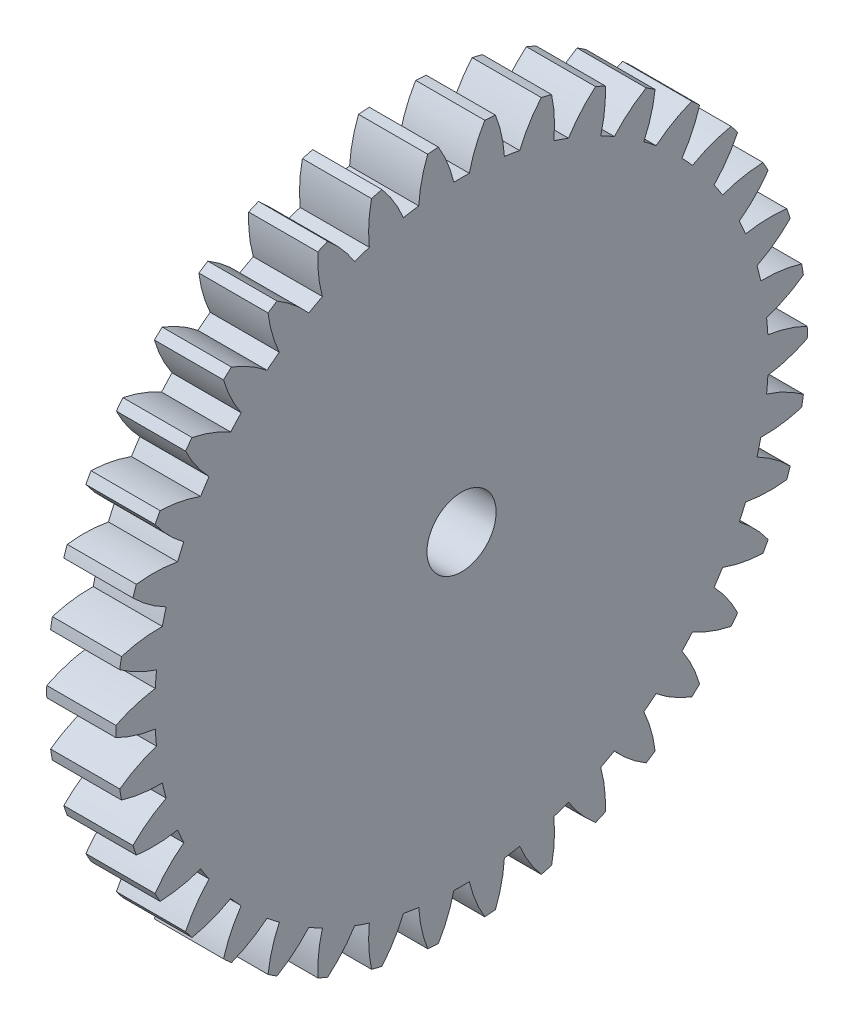
SolidWorks part; units mm, degrees
ref_plane "Plane1" through (0, 0, 0) normal (0, 0, 1) x (1, 0, 0)
ref_plane "Plane2" through (0, 0, 0) normal (0, 1, 0) x (1, 0, 0)
ref_plane "Plane3" through (0, 0, 0) normal (1, 0, 0) x (0, 0, -1)
other "Configuration Table"
sketch "HoldingSke" plane through (0, 0, 0) normal (0, 1, 0) x (1, 0, 0)
  line L0 (0, 0) -> (320.2476, -250.2048)
  line L1 (-15, 0) -> (100, 0) construction
  line L2 (0, 0) -> (-2.1039, 2.3779)
  line L3 (0, 0) -> (-11.863, 4.5341)
  line L4 (0, 0) -> (6.8053, 5.3169)
  line L5 (0, 0) -> (-47.5972, -17.7524)
  line L6 (0, 0) -> (-5.2639, -3.5516)
  line L7 (-2.1039, 2.3779) -> (8.8308, 51.9871)
  line L8 (-76.2, 54.61) -> (-69.596, 54.61)
  line L9 (-71.009, 38.7566) -> (-53.1078, 45.2721)
  line L10 (-76.2, 71.12) -> (104.1128, 71.12)
  line L11 (0, 0) -> (-6.35, 0)
  line L12 (-76.2, 101.6) -> (-76.1428, 101.6)
  line L13 (24.9733, 27.94) -> (52.9518, 28.4284)
  line L14 (24.9733, 27.94) -> (24.9746, 27.94)
  line L15 (24.9733, 27.94) -> (100.4006, 29.5858)
  circle A0 centre (0, 0) radius 3.175
  circle A1 centre (0, 0) radius 28.1769
  circle A2 centre (0, 0) radius 38.1
  circle A3 centre (0, 0) radius 3.175
  dimension "MHD" = 56.3537
  dimension "Hub_dia" = 76.2
  dimension "Bore" = 6.35
  dimension "MBD" = 6.35
  dimension "Num_teeth" = 38
  dimension "Pitch" = 406.4
  dimension "Overall_len" = 50.8
  dimension "Show_teeth" = 38
  dimension "Thickness" = 6.35
  dimension "OAL" = 50.8001
  dimension "T_dim" = 6.604
  dimension "Ap" = 20
  dimension "H" = 19.05
  dimension "Pitch_radius" = 180.3128
  dimension "Width" = 6.35
  dimension "Backlash" = 0.0571
  dimension "Addendum_fac" = 1
  dimension "Dedendum_fac" = 1.25
  dimension "Clearance_fac" = 0.25
  dimension "Dedendum_add" = 0.0013
sketch "BasProSke" plane through (0, 0, 0) normal (0, 1, 0) x (1, 0, 0)
  line L0 (-10, 0) -> (60, 0) construction
  line L1 (0, 0) -> (0, 31.75)
  line L2 (0, 0) -> (6.35, 0)
  line L3 (6.35, 0) -> (6.35, 31.75)
  line L4 (6.35, 31.75) -> (0, 31.75)
  dimension "Thickness" = 6.35
  dimension "Diameter" = 63.5
revolve "Base-Revolve" add sketch "BasProSke" angle 360 about L0
sketch "TooCutSke" plane through (0, 0, 0) normal (1, 0, 0) x (0, 0, -1)
  line L1 (0, 0) -> (0, 107) construction
  line L2 (0, 0) -> (-1.3465, 30.1324) construction
  line L3 (0, 0) -> (-4.978, 60.0755) construction
  line L4 (-1.3465, 30.1324) -> (-2.489, 30.0378) construction
  arc A0 (0.7117, 28.1679) -> (-0.7117, 28.1679) centre (0, 0) ccw
  arc A1 (2.1467, 31.7028) -> (-2.1467, 31.7028) centre (0, 0) ccw
  circle A2 centre (0, 0) radius 30.1625 construction
  circle A3 centre (0, 0) radius 28.3435 construction
  arc A4 (-0.7117, 28.1679) -> (-2.1467, 31.7028) centre (-12.4675, 25.4541) ccw
  arc A5 (2.1467, 31.7028) -> (0.7117, 28.1679) centre (12.4675, 25.4541) ccw
  dimension "Root_dia" = 56.3537
  dimension "Overcut_dia" = 63.5508
  dimension "Pitch_dia" = 60.325
  dimension "Base_dia" = 56.687
  dimension "Flank_rad" = 12.065
  dimension "Half_ang" = 4.737
  dimension "Half_CT" = 1.1465
extrude "ToothCut" cut sketch "TooCutSke" along normal through all
fillet "Breaks" [suppressed] radius 0.0318
fillet "RootFillets" [suppressed] radius 0.3981
pattern_circular "TeethCuts" count 38 every 9.474 about axis through (-10, 0, 0) along (1, 0, 0) of "ToothCut", "RootFillets", "Breaks"
sketch "HubNeaOneSke" plane through (0, 0, 0) normal (-1, 0, 0) x (0, 0, 1)
  circle A0 centre (0, 0) radius 28.1769
  dimension "Diameter" = 56.3537
extrude "HubNearOne" [suppressed] add sketch "HubNeaOneSke" along normal blind 44.4501
sketch "HubNeaBotSke" plane through (0, 0, 0) normal (-1, 0, 0) x (0, 0, 1)
  circle A0 centre (0, 0) radius 28.1769
  dimension "Diameter" = 56.3537
extrude "HubNearBoth" [suppressed] add sketch "HubNeaBotSke" along normal blind 22.225
ref_plane "FarPln" through (6.35, 0, 0) normal (1, 0, 0) x (0, 0, -1)
sketch "HubFarSke" plane through (6.35, 0, 0) normal (1, 0, 0) x (0, 0, -1)
  circle A0 centre (0, 0) radius 28.1769
  dimension "Diameter" = 56.3537
extrude "HubFar" [suppressed] add sketch "HubFarSke" along normal blind 22.225
sketch "BorSke" plane through (0, 0, 0) normal (1, 0, 0) x (0, 0, -1)
  circle A0 centre (0, 0) radius 3.175
  dimension "Diameter" = 6.35
extrude "Bore" cut sketch "BorSke" along normal mid plane 101.6001
sketch "KeySke" plane through (0, 0, 0) normal (1, 0, 0) x (0, 0, -1)
  line L0 (-0.127, 0) -> (-0.127, 3.429)
  line L1 (-0.127, 3.429) -> (0.127, 3.429)
  line L2 (0.127, 3.429) -> (0.127, 0)
  line L3 (0, 0) -> (0, 34) construction
  line L4 (-0.127, 0) -> (0.127, 0)
  dimension "Offset" = 3.429
  dimension "Width" = 0.254
extrude "Keyway" [suppressed] cut sketch "KeySke" along normal mid plane 101.6001
pattern_circular "Keyway2" [suppressed] count 2 every 90 about axis through (-10, 0, 0) along (1, 0, 0)
equation "' \"Pitch@HoldingSke\" = 4"
equation "' \"Num_teeth@HoldingSke\" = 12"
equation "' \"Ap@HoldingSke\" =  20"
equation "' \"Ap@HoldingSke\" = 20"
equation "' \"Width@HoldingSke\" = 0.5"
equation "' \"Hub_dia@HoldingSke\"= 1"
equation "' \"Hub_dia@HoldingSke\" = 1"
equation "' \"Overall_len@HoldingSke\" = 1.0"
equation "' \"Bore@HoldingSke\" = 0.75"
equation "' \"T_dim@HoldingSke\" = 0.85"
equation "' \"Width@KeySke\" = 0.25"
equation "' \"Show_teeth@HoldingSke\" = 13"
equation "' \"Backlash@HoldingSke\" = 0.009"
equation "' \"Addendum_fac@HoldingSke\" = 1.0"
equation "' \"Dedendum_fac@HoldingSke\" = 1.25"
equation "' \"Dedendum_add@HoldingSke\" = 0.00005"
equation "' \"Clearance_fac@HoldingSke\" = 0.25"
equation "' \"Pitch@HoldingSke\" = 0.5"
equation "' \"Num_teeth@HoldingSke\" = 23"
equation "' \"Show_teeth@HoldingSke\" = 23"
equation "' \"Backlash@HoldingSke\" = 0.0375"
equation "\"Overcut_dia@TooCutSke\" = (\"Num_teeth@HoldingSke\" + 2 * \"Addendum_fac@HoldingSke\") / \"Pitch@HoldingSke\" + 0.002"
equation "\"Pitch_dia@TooCutSke\" = \"Num_teeth@HoldingSke\" / \"Pitch@HoldingSke\""
equation "\"Base_dia@TooCutSke\" = \"Num_teeth@HoldingSke\" / \"Pitch@HoldingSke\" * cos((\"Ap@HoldingSke\"  * 3.14159265 / 180))"
equation "\"Root_dia@TooCutSke\" = (\"Num_teeth@HoldingSke\" + 2) / \"Pitch@HoldingSke\" - 2 * (\"Addendum_fac@HoldingSke\" + \"Dedendum_fac@HoldingSke\") / \"Pitch@HoldingSke\" - \"Dedendum_add@HoldingSke\" * 2"
equation "\"Half_ang@TooCutSke\" = 180 / \"Num_teeth@HoldingSke\""
equation "\"Half_CT@TooCutSke\" = \"Num_teeth@HoldingSke\" / \"Pitch@HoldingSke\" * sin((3.14159265 / 2 / \"Num_teeth@HoldingSke\")) / 2 - 7 * \"Backlash@HoldingSke\" / 4"
equation "\"Flank_rad@TooCutSke\" = \"Num_teeth@HoldingSke\" / \"Pitch@HoldingSke\" / 5"
equation "\"Radius@RootFillets\" = \"Clearance_fac@HoldingSke\" / \"Pitch@HoldingSke\" + \"Dedendum_add@HoldingSke\""
equation "\"Break_rad@Breaks\" = 0.02 / \"Pitch@HoldingSke\""
equation "\"Thickness@HoldingSke\" = \"Width@HoldingSke\""
equation "\"OAL@HoldingSke\" = \"Thickness@HoldingSke\""
equation "\"MHD@HoldingSke\" = (\"Num_teeth@HoldingSke\" + 2) / \"Pitch@HoldingSke\" - 2 * (\"Addendum_fac@HoldingSke\" + \"Dedendum_fac@HoldingSke\")  / \"Pitch@HoldingSke\" - \"Dedendum_add@HoldingSke\" * 2"
equation "\"MBD@HoldingSke\" = (\"Num_teeth@HoldingSke\" + 2) / \"Pitch@HoldingSke\" - 2 * (\"Addendum_fac@HoldingSke\" + \"Dedendum_fac@HoldingSke\")  / \"Pitch@HoldingSke\" - \"Dedendum_add@HoldingSke\" * 2 - 0.002"
equation "\"MHD@HoldingSke\" = ((sgn( \"MHD@HoldingSke\" - \"Hub_dia@HoldingSke\" )-1)*( \"MHD@HoldingSke\" - \"Hub_dia@HoldingSke\" ))/-2+ \"Hub_dia@HoldingSke\""
equation "\"MBD@HoldingSke\" = ((sgn( \"MBD@HoldingSke\" - \"Bore@HoldingSke\" )-1)*( \"MBD@HoldingSke\" - \"Bore@HoldingSke\" ))/-2+ \"Bore@HoldingSke\""
equation "\"OAL@HoldingSke\" = ((sgn( \"OAL@HoldingSke\" - \"Overall_len@HoldingSke\" )+1)*( \"OAL@HoldingSke\" - \"Overall_len@HoldingSke\" ))/2 + \"Overall_len@HoldingSke\" + 0.000002"
equation "\"Num_teeth@TeethCuts\" = int( \"Show_teeth@HoldingSke\" ) + 1"
equation "\"Num_teeth@TeethCuts\" = ((sgn( \"Num_teeth@TeethCuts\" - \"Num_teeth@HoldingSke\" )-1)*( \"Num_teeth@TeethCuts\" - \"Num_teeth@HoldingSke\" ))/-2+ \"Num_teeth@HoldingSke\""
equation "\"Num_teeth@TeethCuts\" = ((sgn( \"Num_teeth@TeethCuts\" - 2.0)+1)*( \"Num_teeth@TeethCuts\" - 2.0))/2 +2.0"
equation "\"Angle@TeethCuts\" = 360.0 / \"Num_teeth@HoldingSke\""
equation "\"Diameter@BasProSke\" = (\"Num_teeth@HoldingSke\" + 2 * \"Addendum_fac@HoldingSke\") / \"Pitch@HoldingSke\""
equation "\"Thickness@BasProSke\"  = \"Thickness@HoldingSke\""
equation "' \"Fillet_rad@BasProSke\" =  \"Thickness@HoldingSke\" * 0.05"
equation "' \"Fillet_rad@BasProSke\" = \"Thickness@HoldingSke\" * 0.05"
equation "\"MHD@HoldingSke\" = ((sgn( \"MHD@HoldingSke\" - \"Root_dia@TooCutSke\" )-1)*( \"MHD@HoldingSke\" - \"Root_dia@TooCutSke\" ))/-2+ \"Root_dia@TooCutSke\""
equation "\"Diameter@HubNeaOneSke\" = \"MHD@HoldingSke\""
equation "\"Length@HubNearOne\" = \"OAL@HoldingSke\" - \"Thickness@BasProSke\""
equation "\"Diameter@HubNeaBotSke\" = \"MHD@HoldingSke\""
equation "\"Length@HubNearBoth\" = ( \"OAL@HoldingSke\" - \"Thickness@BasProSke\" ) / 2.0"
equation "\"Thickness@FarPln\" = \"Thickness@BasProSke\""
equation "\"Diameter@HubFarSke\" = \"MHD@HoldingSke\""
equation "\"Length@HubFar\" = ( \"OAL@HoldingSke\" - \"Thickness@BasProSke\" ) / 2.0"
equation "\"Diameter@BorSke\" = \"MBD@HoldingSke\""
equation "\"D1@Bore\" = \"OAL@HoldingSke\" * 2.0"
equation "\"D1@Keyway\" = \"OAL@HoldingSke\" * 2.0"
equation "\"Offset@KeySke\" = \"T_dim@HoldingSke\" - \"MBD@HoldingSke\" / 2.0"
